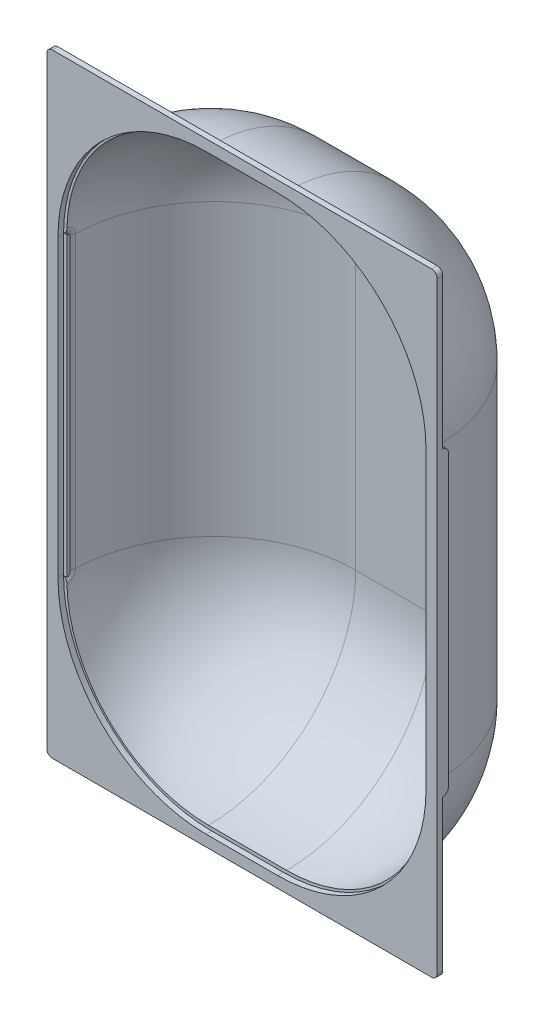
SolidWorks part; units mm, degrees
ref_plane "Front Plane" through (0, 0, 0) normal (0, 0, 1) x (1, 0, 0)
ref_plane "Top Plane" through (0, 0, 0) normal (0, 1, 0) x (1, 0, 0)
ref_plane "Right Plane" through (0, 0, 0) normal (1, 0, 0) x (0, 0, -1)
sketch "Sketch1" plane through (0, 0, 0) normal (0, 1, 0) x (1, 0, 0)
  line L0 (0.3505, 3) -> (0.3505, 3)
  line L1 (0, 0) -> (330, 0)
  line L3 (130, 135) -> (200, 135)
  line L5 (332.9662, 5) -> (340, 5)
  line L7 (330, 0) -> (340, 0)
  line L8 (340, 5) -> (340, 0)
  line L9 (0, 0) -> (-10, 0)
  line L11 (-2.9662, 5) -> (-10, 5)
  line L12 (-10, 0) -> (-10, 5)
  line L13 (0.3505, 3) -> (0.3505, 3)
  line L14 (0.3505, 3) -> (0.3505, 3)
  line L15 (0.3505, 3) -> (329.6495, 3)
  line L16 (329.6495, 3) -> (329.6495, 3)
  line L17 (329.6495, 3) -> (329.6495, 3)
  line L18 (329.6495, 3) -> (329.6495, 3)
  line L19 (130, 132) -> (200, 132)
  arc A0 (130, 135) -> (0.0331, 7.9323) centre (130, 5) ccw
  arc A1 (329.9669, 7.9323) -> (200, 135) centre (200, 5) ccw
  arc A2 (332.9662, 5) -> (329.9669, 7.9323) centre (332.9662, 8) cw
  arc A3 (0.0331, 7.9323) -> (-2.9662, 5) centre (-2.9662, 8) cw
  arc A4 (130, 132) -> (3.0323, 7.8647) centre (130, 5) ccw
  arc A5 (3.0323, 7.8647) -> (0.3505, 3) centre (-2.9662, 8) cw
  arc A6 (329.6495, 3) -> (326.9677, 7.8647) centre (332.9662, 8) cw
  arc A7 (326.9677, 7.8647) -> (200, 132) centre (200, 5) ccw
  point P7 (0, 135)
  point P10 (330, 135)
  dimension "D3" = 130
  dimension "D4" = 130
  dimension "D5" = 3
  dimension "D6" = 3
  dimension "D1" = 135
  dimension "D2" = 330
  dimension "D7" = 3
extrude "Boss-Extrude1" add sketch "Sketch1" along normal blind 260
sketch "Sketch2" plane through (0, 260, 0) normal (0, 1, 0) x (1, 0, 0)
  line L0 (165, 135) -> (165, 0) construction
  line L1 (200, 135) -> (130, 135) construction
  line L2 (-10, 0) -> (340, 0) construction
  line L4 (129.5043, 135) -> (200.4957, 135)
  line L5 (-0.4957, 5) -> (-0.4957, 0)
  line L6 (-0.4957, 0) -> (330.4957, 0)
  line L7 (330.4957, 5) -> (330.4957, 0)
  line L8 (-0.4957, 135) -> (330.4957, 0) construction
  line L9 (-0.4957, 0) -> (330.4957, 135) construction
  line L10 (-10, 5) -> (-0.4957, 5)
  line L11 (-10, 5) -> (-10, 0)
  line L12 (-10, 0) -> (-0.4957, 0)
  line L13 (-0.4957, 5) -> (-0.4957, 0)
  line L14 (340, 5) -> (330.4957, 5)
  line L15 (340, 5) -> (340, 0)
  line L16 (340, 0) -> (330.4957, 0)
  line L17 (330.4957, 5) -> (330.4957, 0)
  arc A0 (129.5043, 135) -> (-0.4957, 5) centre (129.5043, 5) ccw
  arc A1 (330.4957, 5) -> (200.4957, 135) centre (200.4957, 5) ccw
  point P6 (165, 67.5)
  dimension "D1" = 130
  dimension "D2" = 130
sketch "Sketch3" plane through (0, 0, 0) normal (0, -1, 0) x (1, 0, 0)
  line L0 (0, 0) -> (330, 0)
  line L10 (130, -132) -> (200, -132)
  line L11 (0.3505, -3) -> (329.6495, -3)
  line L12 (-10, 0) -> (-10, -5)
  line L13 (-2.9662, -5) -> (-10, -5)
  line L14 (0, 0) -> (-10, 0)
  line L15 (340, -5) -> (340, 0)
  line L16 (330, 0) -> (340, 0)
  line L17 (332.9662, -5) -> (340, -5)
  line L18 (130, -135) -> (200, -135)
  arc A8 (326.9677, -7.8647) -> (200, -132) centre (200, -5) cw
  arc A9 (329.6495, -3) -> (326.9677, -7.8647) centre (332.9662, -8) ccw
  arc A10 (3.0323, -7.8647) -> (0.3505, -3) centre (-2.9662, -8) ccw
  arc A11 (130, -132) -> (3.0323, -7.8647) centre (130, -5) cw
  arc A12 (0.0331, -7.9323) -> (-2.9662, -5) centre (-2.9662, -8) ccw
  arc A13 (332.9662, -5) -> (329.9669, -7.9323) centre (332.9662, -8) ccw
  arc A14 (329.9669, -7.9323) -> (200, -135) centre (200, -5) cw
  arc A15 (130, -135) -> (0.0331, -7.9323) centre (130, -5) cw
  point P72 (330, -135)
  point P73 (0, -135)
revolve "Revolve1" add sketch "Sketch3" angle 90 about L0
sketch "Sketch4" plane through (0, 260, 0) normal (0, 1, 0) x (1, 0, 0)
  line L0 (0, 0) -> (330, 0)
  line L1 (130, 135) -> (200, 135)
  line L2 (332.9662, 5) -> (340, 5)
  line L3 (330, 0) -> (340, 0)
  line L4 (340, 5) -> (340, 0)
  line L5 (0, 0) -> (-10, 0)
  line L6 (-2.9662, 5) -> (-10, 5)
  line L7 (-10, 0) -> (-10, 5)
  line L8 (0.3505, 3) -> (329.6495, 3)
  line L9 (130, 132) -> (200, 132)
  arc A0 (130, 135) -> (0.0331, 7.9323) centre (130, 5) ccw
  arc A1 (329.9669, 7.9323) -> (200, 135) centre (200, 5) ccw
  arc A2 (332.9662, 5) -> (329.9669, 7.9323) centre (332.9662, 8) cw
  arc A3 (0.0331, 7.9323) -> (-2.9662, 5) centre (-2.9662, 8) cw
  arc A4 (130, 132) -> (3.0323, 7.8647) centre (130, 5) ccw
  arc A5 (3.0323, 7.8647) -> (0.3505, 3) centre (-2.9662, 8) cw
  arc A6 (329.6495, 3) -> (326.9677, 7.8647) centre (332.9662, 8) cw
  arc A7 (326.9677, 7.8647) -> (200, 132) centre (200, 5) ccw
  point P6 (0, 135)
  point P9 (330, 135)
  dimension "D3" = 130
  dimension "D4" = 3
  dimension "D5" = 3
  dimension "D1" = 135
  dimension "D2" = 330
revolve "Revolve2" add sketch "Sketch4" angle 90 about L0
sketch "Sketch5" plane through (0, 0, 0) normal (0, 0, 1) x (1, 0, 0)
  line L0 (0.3505, -3) -> (329.6495, -3) construction
  line L1 (3.0217, 263) -> (326.9677, 263)
  line L2 (3.0217, 263) -> (3.0217, -3)
  line L3 (3.0217, -3) -> (326.9677, -3)
  line L4 (326.9677, 263) -> (326.9677, -3)
  line L5 (326.9677, -7.8647) -> (326.9677, 0) construction
  line L6 (0.3505, 263) -> (329.6495, 263) construction
  point P9 (3.0217, 263)
extrude "Cut-Extrude1" cut sketch "Sketch5" against normal blind 5
sketch "Sketch6" plane through (0, 0, 0) normal (0, 0, 1) x (1, 0, 0)
  line L0 (-10, 130) -> (340, 130) construction
  line L1 (-10, 265) -> (-10, -5) construction
  line L2 (340, 265) -> (340, -5) construction
  line L4 (133, -135.0098) -> (197, -135.0098)
  line L5 (0, -2.0098) -> (0, 262.0098)
  line L6 (133, 395.0098) -> (197, 395.0098)
  line L7 (330, -2.0098) -> (330, 262.0098)
  line L8 (0, -135.0098) -> (330, 395.0098) construction
  line L9 (0, 395.0098) -> (330, -135.0098) construction
  line L10 (-10, -145) -> (340, -145)
  line L11 (-10, -145) -> (-10, 405)
  line L12 (-10, 405) -> (340, 405)
  line L13 (340, -145) -> (340, 405)
  line L14 (-10, -145) -> (340, 405) construction
  line L15 (-10, 405) -> (340, -145) construction
  arc A0 (133, 395.0098) -> (0, 262.0098) centre (133, 262.0098) ccw
  arc A1 (330, 262.0098) -> (197, 395.0098) centre (197, 262.0098) ccw
  arc A2 (197, -135.0098) -> (330, -2.0098) centre (197, -2.0098) ccw
  arc A3 (0, -2.0098) -> (133, -135.0098) centre (133, -2.0098) ccw
  point P6 (165, 130)
  point P23 (165, 130)
  dimension "D1" = 133
  dimension "D2" = 133
  dimension "D3" = 133
  dimension "D4" = 133
extrude "Boss-Extrude2" add sketch "Sketch6" along normal blind 5
fillet "Fillet1" radius 5 4 edges at (340, 405, 2.5) (-10, 405, 2.5) (-10, -145, 2.5) (340, -145, 2.5)
